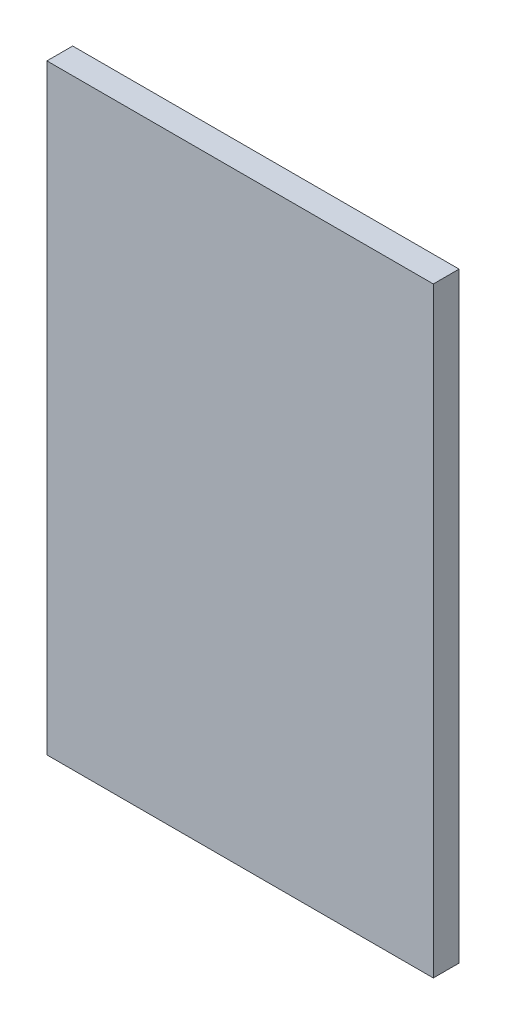
SolidWorks part; units mm, degrees
ref_plane "Alzado" through (0, 0, 0) normal (0, 0, 1) x (1, 0, 0)
ref_plane "Planta" through (0, 0, 0) normal (0, 1, 0) x (1, 0, 0)
ref_plane "Vista lateral" through (0, 0, 0) normal (1, 0, 0) x (0, 0, -1)
sketch "Croquis1" plane through (0, 0, 0) normal (0, 0, 1) x (1, 0, 0)
  line L1 (22.5, -35) -> (-22.5, -35)
  line L2 (22.5, -35) -> (22.5, 35)
  line L3 (22.5, 35) -> (-22.5, 35)
  line L4 (-22.5, -35) -> (-22.5, 35)
  line L5 (22.5, -35) -> (-22.5, 35) construction
  line L6 (22.5, 35) -> (-22.5, -35) construction
  point P0 (0, 0)
  dimension "D1" = 45
  dimension "D2" = 70
extrude "Saliente-Extruir1" add sketch "Croquis1" along normal blind 3
